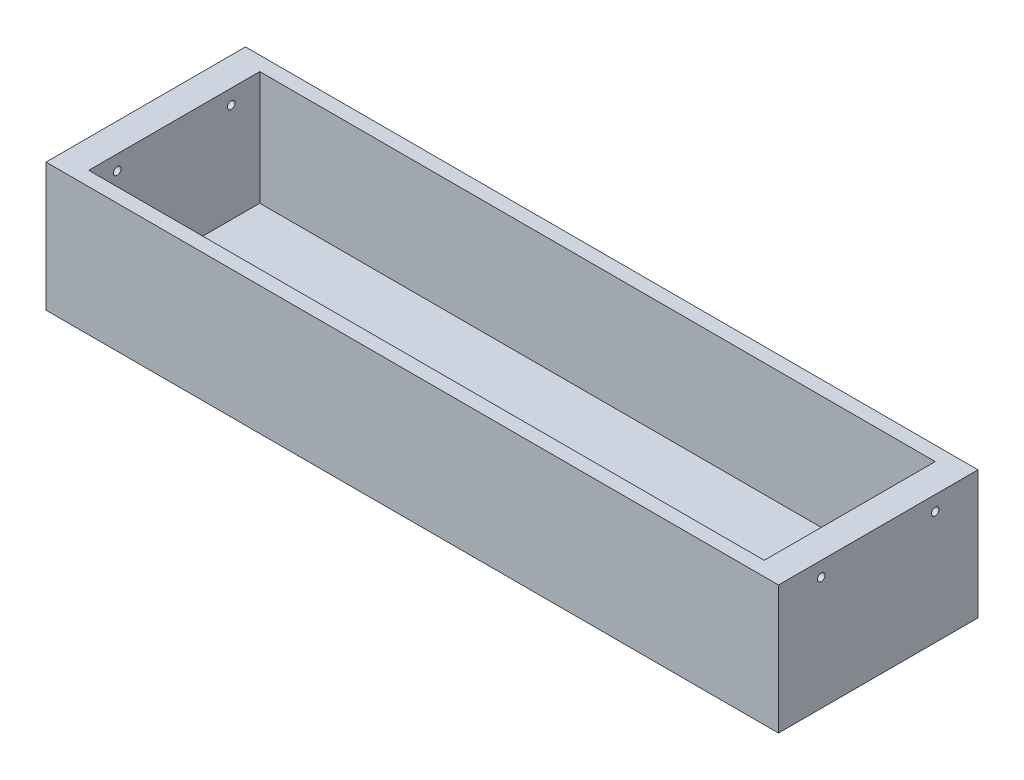
SolidWorks part; units mm, degrees
ref_plane "Front Plane" through (0, 0, 0) normal (0, 0, 1) x (1, 0, 0)
ref_plane "Top Plane" through (0, 0, 0) normal (0, 1, 0) x (1, 0, 0)
ref_plane "Right Plane" through (0, 0, 0) normal (1, 0, 0) x (0, 0, -1)
sketch "Sketch1" plane through (0, 0, 0) normal (0, 1, 0) x (1, 0, 0)
  line L1 (-131.445, -31.75) -> (131.445, -31.75) construction
  line L2 (-131.445, -31.75) -> (-131.445, 31.75) construction
  line L3 (-131.445, 31.75) -> (131.445, 31.75) construction
  line L4 (131.445, -31.75) -> (131.445, 31.75) construction
  line L5 (0, 31.75) -> (0, -31.75) construction
  line L6 (-131.445, 0) -> (131.445, 0) construction
  line L11 (-163.195, -44.45) -> (163.195, -44.45)
  line L12 (-163.195, -44.45) -> (-163.195, 44.45)
  line L13 (-163.195, 44.45) -> (163.195, 44.45)
  line L14 (163.195, -44.45) -> (163.195, 44.45)
  line L15 (0, 44.45) -> (0, -44.45) construction
  line L16 (-163.195, 0) -> (163.195, 0) construction
  line L17 (-150.495, -38.1) -> (150.495, -38.1)
  line L18 (-150.495, -38.1) -> (-150.495, 38.1)
  line L23 (0, 38.1) -> (0, -38.1) construction
  line L24 (-150.495, 0) -> (150.495, 0) construction
  line L25 (-150.495, 38.1) -> (150.495, 38.1)
  line L26 (150.495, -38.1) -> (150.495, 38.1)
  line L27 (0, 38.1) -> (0, -38.1) construction
  line L28 (-150.495, 0) -> (150.495, 0) construction
  point P0 (0, 0)
  point P4 (0, 0)
  point P8 (0, 0)
  point P13 (0, 0)
  dimension "D1" = 131.445
  dimension "D2" = 63.5
  dimension "D4" = 6.35
  dimension "D5" = 12.7
  dimension "D3" = 19.05
  dimension "D6" = 6.35
extrude "Boss-Extrude1" add sketch "Sketch1" along normal blind 50.8
sketch "Sketch2" plane through (0, 0, 0) normal (0, -1, 0) x (1, 0, 0)
  line L4 (163.195, -44.45) -> (163.195, 44.45)
  line L5 (163.195, 44.45) -> (-163.195, 44.45)
  line L6 (-163.195, 44.45) -> (-163.195, -44.45)
  line L7 (-163.195, -44.45) -> (163.195, -44.45)
  line L8 (163.195, -44.45) -> (163.195, 44.45)
  line L9 (163.195, 44.45) -> (-163.195, 44.45)
  line L10 (-163.195, 44.45) -> (-163.195, -44.45)
  line L11 (-163.195, -44.45) -> (163.195, -44.45)
  dimension "D1" = 0
extrude "Boss-Extrude2" add sketch "Sketch2" along normal blind 6.35
sketch "Sketch3" plane through (0, -6.35, 0) normal (0, -1, 0) x (1, 0, 0)
  line L0 (55, 0) -> (-55, 0) construction
  circle A0 centre (-106, 7.5) radius 3.1
  circle A1 centre (-106, -7.5) radius 3.1
  point P7 (105.9993, 10.2747)
  point P8 (-104.802, 16.8863)
  dimension "D2" = 6.2
  dimension "D1" = 106
  dimension "D3" = 7.5
extrude "Cut-Extrude1" cut sketch "Sketch3" against normal through all
sketch "Sketch4" plane through (163.195, 0, 0) normal (1, 0, 0) x (0, 0, -1)
  line L0 (44.45, -6.35) -> (-44.45, -6.35) construction
  line L1 (0, 55) -> (0, -55) construction
  circle A0 centre (25.4, 44.2239) radius 1.6875
  circle A1 centre (-25.4, 44.2239) radius 1.6875
  dimension "D2" = 3.375
  dimension "D1" = 50.5739
  dimension "D3" = 25.4
extrude "Cut-Extrude3" cut sketch "Sketch4" against normal up to surface (313.69 mm away)
mirror "Mirror2" about plane through (0, 0, 0) normal (1, 0, 0) of "Cut-Extrude3"
